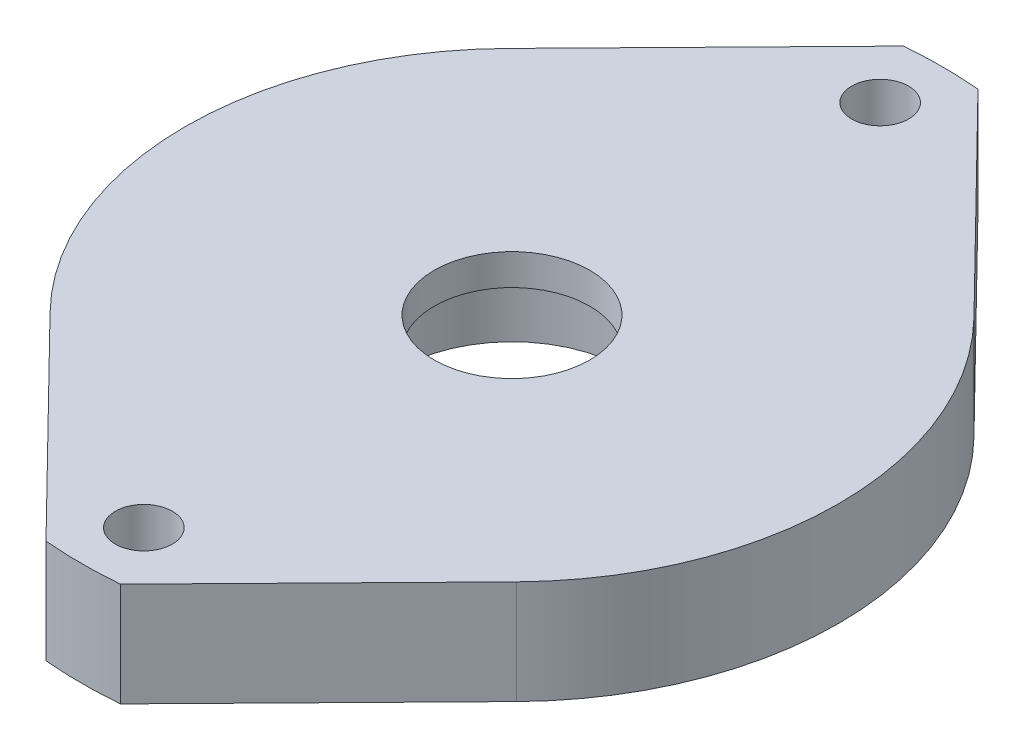
SolidWorks part; units mm, degrees
material "AU4G - 2017A"
ref_plane "Plan de face" through (0, 0, 0) normal (0, 0, 1) x (1, 0, 0)
ref_plane "Plan de dessus" through (0, 0, 0) normal (0, 1, 0) x (1, 0, 0)
ref_plane "Plan de droite" through (0, 0, 0) normal (1, 0, 0) x (0, 0, -1)
sketch "Sketch1" plane through (0, 0, 0) normal (0, 1, 0) x (1, 0, 0)
  circle A0 centre (0, 0) radius 41.5
  dimension "D1" = 83
extrude "Boss-Extrude1" add sketch "Sketch1" along normal blind 10
sketch "Sketch2" plane through (0, 0, 0) normal (0, -1, 0) x (1, 0, 0)
  line L0 (-22.5, 22.0454) -> (-3.591, 41.3443)
  line L1 (22.5, 22.0454) -> (3.591, 41.3443)
  line L2 (0, 0) -> (0, 12.7475) construction
  line L3 (0, 0) -> (14.4007, 0) construction
  line L4 (22.5, -22.0454) -> (3.591, -41.3443)
  line L5 (-22.5, -22.0454) -> (-3.591, -41.3443)
  circle A1 centre (0, 0) radius 41.5 construction
  arc A2 (-22.5, 22.0454) -> (-22.5, -22.0454) centre (0, 0) ccw
  arc A3 (3.591, 41.3443) -> (-3.591, 41.3443) centre (0, 0) ccw
  arc A4 (3.591, -41.3443) -> (-3.591, -41.3443) centre (0, 0) cw
  arc A5 (22.5, -22.0454) -> (22.5, 22.0454) centre (0, 0) ccw
  dimension "D1" = 63
  dimension "D3" = 45
extrude "Cut-Extrude1" cut sketch "Sketch2" against normal blind 10 flip side to cut
sketch "Sketch3" plane through (0, 0, 0) normal (0, 1, 0) x (1, 0, 0)
  circle A1 centre (0, 0) radius 11
  dimension "D1" = 22
extrude "Cut-Extrude2" cut sketch "Sketch3" along normal blind 7
sketch "Sketch4" plane through (0, 7, 0) normal (0, -1, 0) x (1, 0, 0)
  circle A0 centre (0, 0) radius 7.5
  dimension "D1" = 15
extrude "Cut-Extrude3" cut sketch "Sketch4" against normal up to next
hole_wizard "M5 Clearance Hole1" positions "Sketch6" profile "Sketch5" hole size "M5" standard "ISO" end condition through all
sketch "Sketch6" plane through (0, 0, 0) normal (0, -1, 0) x (-1, 0, 0)
  point P0 (0, 35.5)
  point P3 (0, -35.5)
sketch "Sketch5" plane through (0, 0, -35.5) normal (1, 0, 0) x (0, 0, -1)
  line L0 (0, 0) -> (0, 10)
  line L1 (0, 10) -> (2.75, 10)
  line L2 (2.75, 10) -> (2.75, 0)
  line L5 (2.75, 0) -> (0, 0)
  line L11 (0, -6.35) -> (0, 107.95) construction
  dimension "Thru Hole Dia." = 5.5
  dimension "Thru Hole Depth" = 10
